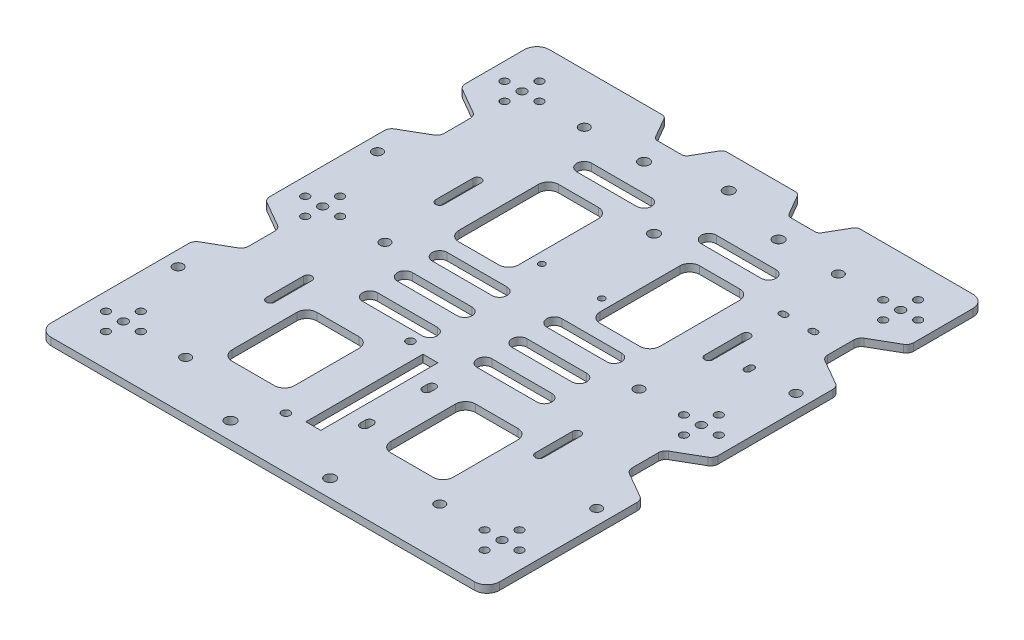
SolidWorks part; units mm, degrees
ref_plane "Front Plane" through (0, 0, 0) normal (0, 0, 1) x (1, 0, 0)
ref_plane "Top Plane" through (0, 0, 0) normal (0, 1, 0) x (1, 0, 0)
ref_plane "Right Plane" through (0, 0, 0) normal (1, 0, 0) x (0, 0, -1)
sketch "草图1" plane through (0, 0, 0) normal (0, 1, 0) x (1, 0, 0)
  line L0 (-76, 110.058) -> (-76, -117.2518) construction
  line L1 (-90, -100) -> (90, -100)
  line L2 (-90, -100) -> (-90, 100)
  line L3 (-90, 100) -> (90, 100)
  line L4 (90, -100) -> (90, 100)
  line L5 (-90, -100) -> (90, 100) construction
  line L6 (-90, 100) -> (90, -100) construction
  line L7 (0, 114.4164) -> (0, -117.2518) construction
  line L8 (-86, 80) -> (-48.9187, 80) construction
  line L9 (-76, 0) -> (-83, 0) construction
  line L10 (-76, -40) -> (18.6433, -40) construction
  line L11 (76, 0) -> (83, 0) construction
  circle A0 centre (-76, 80) radius 10 construction
  circle A2 centre (-76, 80) radius 1.75
  circle A3 centre (-83, 80) radius 1.6
  circle A4 centre (-76, 87) radius 1.6
  circle A5 centre (-69, 80) radius 1.6
  circle A6 centre (-76, 73) radius 1.6
  circle A7 centre (-76, 0) radius 1.75
  circle A8 centre (-83, 0) radius 1.6
  circle A9 centre (-76, 0) radius 10 construction
  circle A10 centre (-76, 7) radius 1.6
  circle A11 centre (-76, -7) radius 1.6
  circle A12 centre (-69, 0) radius 1.6
  circle A13 centre (-76, -80) radius 10 construction
  circle A14 centre (-76, -73) radius 1.6
  circle A15 centre (-69, -80) radius 1.6
  circle A16 centre (-76, -80) radius 1.75
  circle A17 centre (-83, -80) radius 1.6
  circle A18 centre (-76, -87) radius 1.6
  circle A19 centre (76, -80) radius 10 construction
  circle A20 centre (76, 0) radius 10 construction
  circle A21 centre (76, 80) radius 10 construction
  circle A22 centre (76, -87) radius 1.6
  circle A23 centre (83, -80) radius 1.6
  circle A24 centre (76, -80) radius 1.75
  circle A25 centre (69, -80) radius 1.6
  circle A26 centre (76, -73) radius 1.6
  circle A27 centre (69, 0) radius 1.6
  circle A28 centre (76, -7) radius 1.6
  circle A29 centre (76, 7) radius 1.6
  circle A30 centre (83, 0) radius 1.6
  circle A31 centre (76, 0) radius 1.75
  circle A32 centre (76, 73) radius 1.6
  circle A33 centre (69, 80) radius 1.6
  circle A34 centre (76, 87) radius 1.6
  circle A35 centre (83, 80) radius 1.6
  circle A36 centre (76, 80) radius 1.75
  point P0 (0, 0)
  point P31 (-76, 0)
  point P81 (76, 0)
  dimension "D4" = 20
  dimension "D5" = 20
  dimension "D6" = 3.5
  dimension "D7" = 3.2
  dimension "D8" = 14
  dimension "D9" = 3.2
  dimension "D10" = 14
  dimension "D11" = 3.5
  dimension "D12" = 80
  dimension "D13" = 3.2
  dimension "D14" = 7
  dimension "D15" = 20
  dimension "D16" = 80
  dimension "D17" = 3.2
  dimension "D18" = 7
  dimension "D19" = 20
  dimension "D1" = 200
  dimension "D2" = 180
  dimension "D3" = 14
  dimension "D21" = 40
extrude "凸台-拉伸1" add sketch "草图1" along normal blind 3
sketch "草图2" plane through (0, 3, 0) normal (0, 1, 0) x (1, 0, 0)
  line L0 (-51, 100) -> (-51, -121.0389) construction
  line L1 (90, 100) -> (-90, 100) construction
  line L2 (0, 100) -> (0, -100) construction
  line L3 (-90, -100) -> (90, -100) construction
  line L4 (-90, 100) -> (-90, -100) construction
  line L5 (-118.3864, 0) -> (145.0738, 0) construction
  line L6 (51, 100) -> (51, -121.0389) construction
  circle A0 centre (-84, 30) radius 2
  circle A1 centre (-84, -50) radius 2
  circle A3 centre (-51, 0) radius 2
  circle A4 centre (-51, -80) radius 2
  circle A5 centre (-51, 80) radius 2
  circle A6 centre (51, 80) radius 2
  circle A7 centre (51, -80) radius 2
  circle A8 centre (51, 0) radius 2
  circle A9 centre (84, -50) radius 2
  circle A10 centre (84, 30) radius 2
  dimension "D2" = 4
  dimension "D3" = 6
  dimension "D4" = 30
  dimension "D5" = 4
  dimension "D6" = 50
  dimension "D7" = 6
  dimension "D9" = 4
  dimension "D10" = 4
  dimension "D1" = 39
  dimension "D11" = 20
extrude "切除-拉伸1" cut sketch "草图2" against normal blind 3
sketch "草图3" plane through (0, 3, 0) normal (0, 1, 0) x (1, 0, 0)
  line L0 (0, 100) -> (0, -105.4254) construction
  line L1 (90, 100) -> (-90, 100) construction
  line L2 (-97.7182, 0) -> (114, 0) construction
  line L3 (-54, 25) -> (-54, 40) construction
  line L4 (-55.65, 25) -> (-55.65, 40)
  line L5 (-52.35, 25) -> (-52.35, 40)
  line L6 (-54, -43) -> (-54, -28) construction
  line L7 (-55.65, -43) -> (-55.65, -28)
  line L8 (-52.35, -43) -> (-52.35, -28)
  line L9 (54, -43) -> (54, -28) construction
  line L10 (55.65, -43) -> (55.65, -28)
  line L11 (52.35, -43) -> (52.35, -28)
  line L12 (54, 25) -> (54, 40) construction
  line L13 (55.65, 25) -> (55.65, 40)
  line L14 (52.35, 25) -> (52.35, 40)
  circle A0 centre (-54, 25) radius 1.65 construction
  circle A1 centre (-54, -43) radius 1.65 construction
  circle A2 centre (54, -43) radius 1.65 construction
  circle A3 centre (54, 25) radius 1.65 construction
  arc A4 (-55.65, 25) -> (-52.35, 25) centre (-54, 25) ccw
  arc A5 (-52.35, 40) -> (-55.65, 40) centre (-54, 40) ccw
  arc A6 (-55.65, -43) -> (-52.35, -43) centre (-54, -43) ccw
  arc A7 (-52.35, -28) -> (-55.65, -28) centre (-54, -28) ccw
  circle A8 centre (54, -43) radius 1.65 construction
  circle A9 centre (54, 25) radius 1.65 construction
  arc A10 (55.65, -43) -> (52.35, -43) centre (54, -43) cw
  arc A11 (52.35, -28) -> (55.65, -28) centre (54, -28) cw
  arc A12 (55.65, 25) -> (52.35, 25) centre (54, 25) cw
  arc A13 (52.35, 40) -> (55.65, 40) centre (54, 40) cw
  point P16 (-54, 32.5)
  point P23 (-54, -35.5)
  point P31 (54, -35.5)
  point P37 (54, 32.5)
  dimension "D1" = 3.3
  dimension "D2" = 25
  dimension "D4" = 3.3
  dimension "D5" = 68
  dimension "D6" = 108
  dimension "D3" = 108
  dimension "D7" = 3.3
  dimension "D8" = 15
  dimension "D9" = 3.3
  dimension "D10" = 15
extrude "翅膀孔位" cut sketch "草图3" against normal blind 7.5
sketch "草图4" plane through (0, 3, 0) normal (0, 1, 0) x (1, 0, 0)
  line L0 (0, 0) -> (0, 124.0114) construction
  line L1 (90, 100) -> (-90, 100) construction
  circle A0 centre (0, 87) radius 2.15
  circle A1 centre (0, 57) radius 2.15
  circle A2 centre (-27, 80) radius 2.15
  circle A3 centre (27, 80) radius 2.15
  dimension "D1" = 13
  dimension "D2" = 4.3
  dimension "D3" = 4.3
  dimension "D4" = 30
  dimension "D5" = 4.3
  dimension "D6" = 20
  dimension "D7" = 54
extrude "尾巴孔位" cut sketch "草图4" against normal blind 7.5
sketch "草图5" plane through (0, 3, 0) normal (0, 1, 0) x (1, 0, 0)
  line L0 (0, 100) -> (0, -116.1185) construction
  line L1 (90, 100) -> (-90, 100) construction
  line L3 (-4.5, -31.25) -> (1.5, -31.25)
  line L4 (-4.5, -31.25) -> (-4.5, -78.25)
  line L5 (-4.5, -78.25) -> (1.5, -78.25)
  line L6 (1.5, -31.25) -> (1.5, -78.25)
  line L7 (-4.5, -31.25) -> (1.5, -78.25) construction
  line L8 (-4.5, -78.25) -> (1.5, -31.25) construction
  line L9 (5.91, 100) -> (5.91, -116.1185) construction
  line L10 (-90, -100) -> (90, -100) construction
  point P9 (-1.5, -54.75)
  dimension "D1" = 47
  dimension "D2" = 6
  dimension "D3" = 1.5
  dimension "D4" = 45.25
  dimension "D5" = 5.91
extrude "打印件位" cut sketch "草图5" against normal blind 7.5
ref_plane "对称面" through (0, 0, 0) normal (-1, 0, 0) x (0, 0, 1)
ref_plane "线定位面" through (5.91, 0, 0) normal (-1, 0, 0) x (0, 0, 1)
sketch "草图6" plane through (0, 3, 0) normal (0, 1, 0) x (1, 0, 0)
  line L0 (-1.5, -31.25) -> (-1.5, -78.25) construction
  line L1 (1.5, -31.25) -> (-4.5, -31.25) construction
  line L2 (-4.5, -78.25) -> (1.5, -78.25) construction
  line L3 (-4.5, -31.25) -> (-4.5, -78.25) construction
  line L4 (1.5, -78.25) -> (1.5, -31.25) construction
  line L5 (-19.6713, -54.25) -> (36.5531, -54.25) construction
  line L6 (8.5, -42.75) -> (8.5, -40.75) construction
  line L7 (6.85, -42.75) -> (6.85, -40.75)
  line L8 (10.15, -42.75) -> (10.15, -40.75)
  line L9 (8.5, -65.75) -> (8.5, -67.75) construction
  line L10 (6.85, -65.75) -> (6.85, -67.75)
  line L11 (10.15, -65.75) -> (10.15, -67.75)
  circle A0 centre (8.5, -41.75) radius 1.6 construction
  circle A1 centre (8.5, -66.75) radius 1.6 construction
  circle A2 centre (-11.5, -29.25) radius 1.65
  circle A3 centre (-11.5, -79.25) radius 1.65
  arc A4 (6.85, -42.75) -> (10.15, -42.75) centre (8.5, -42.75) ccw
  arc A5 (10.15, -40.75) -> (6.85, -40.75) centre (8.5, -40.75) ccw
  arc A6 (6.85, -65.75) -> (10.15, -65.75) centre (8.5, -65.75) cw
  arc A7 (10.15, -67.75) -> (6.85, -67.75) centre (8.5, -67.75) cw
  point P22 (8.5, -41.75)
  point P29 (8.5, -66.75)
  dimension "D1" = 3.2
  dimension "D2" = 20
  dimension "D4" = 25
  dimension "D5" = 3.3
  dimension "D6" = 50
  dimension "D7" = 10
  dimension "D3" = 23
  dimension "D8" = 3.3
  dimension "D9" = 2
extrude "打印件孔位" cut sketch "草图6" against normal blind 10
sketch "草图7" plane through (0, 3, 0) normal (0, 1, 0) x (1, 0, 0)
  line L0 (0, -22.5802) -> (0, -128.6812) construction
  line L1 (0, 1.65) -> (0, -1.65) construction
  line L2 (-90, -100) -> (90, -100) construction
  circle A0 centre (-20, -93) radius 2.15
  circle A1 centre (20, -93) radius 2.15
  dimension "D1" = 40
  dimension "D2" = 7
  dimension "D3" = 4.3
extrude "头部孔位" cut sketch "草图7" against normal blind 10
sketch "草图8" plane through (0, 3, 0) normal (0, 1, 0) x (1, 0, 0)
  line L0 (0, 100) -> (0, -147.651) construction
  line L1 (90, 100) -> (-90, 100) construction
  line L2 (-98.7792, 0) -> (126.1621, 0) construction
  line L3 (-40.35, 55) -> (-16.35, 55)
  line L4 (-40.35, 55) -> (-40.35, 15)
  line L5 (-40.35, 15) -> (-16.35, 15)
  line L6 (-16.35, 55) -> (-16.35, 15)
  line L7 (-40.35, 55) -> (-16.35, 15) construction
  line L8 (-40.35, 15) -> (-16.35, 55) construction
  line L9 (-44.35, -38) -> (-19.35, -38)
  line L10 (-44.35, -38) -> (-44.35, -72)
  line L11 (-44.35, -72) -> (-19.35, -72)
  line L12 (-19.35, -38) -> (-19.35, -72)
  line L13 (-44.35, -38) -> (-19.35, -72) construction
  line L14 (-44.35, -72) -> (-19.35, -38) construction
  line L15 (-52.35, 25) -> (-52.35, 40) construction
  line L16 (-52.35, -43) -> (-52.35, -28) construction
  line L17 (-90, -100) -> (90, -100) construction
  line L18 (44.35, -72) -> (19.35, -38) construction
  line L19 (44.35, -38) -> (19.35, -72) construction
  line L20 (40.35, 15) -> (16.35, 55) construction
  line L21 (40.35, 55) -> (16.35, 15) construction
  line L22 (19.35, -38) -> (19.35, -72)
  line L23 (44.35, -72) -> (19.35, -72)
  line L24 (44.35, -38) -> (44.35, -72)
  line L25 (44.35, -38) -> (19.35, -38)
  line L26 (16.35, 55) -> (16.35, 15)
  line L27 (40.35, 15) -> (16.35, 15)
  line L28 (40.35, 55) -> (40.35, 15)
  line L29 (40.35, 55) -> (16.35, 55)
  line L30 (-35, 6) -> (-11, 6) construction
  line L31 (-35, 9) -> (-11, 9)
  line L32 (-35, 3) -> (-11, 3)
  line L33 (-35, -8) -> (-11, -8) construction
  line L34 (-35, -5) -> (-11, -5)
  line L35 (-35, -11) -> (-11, -11)
  line L36 (-111.9755, -15) -> (122.1958, -15) construction
  line L37 (-35, -22) -> (-11, -22) construction
  line L38 (-35, -25) -> (-11, -25)
  line L39 (-35, -19) -> (-11, -19)
  line L40 (35, -22) -> (11, -22) construction
  line L41 (35, -25) -> (11, -25)
  line L42 (35, -19) -> (11, -19)
  line L43 (35, -8) -> (11, -8) construction
  line L44 (35, -5) -> (11, -5)
  line L45 (35, -11) -> (11, -11)
  line L46 (35, 6) -> (11, 6) construction
  line L47 (35, 9) -> (11, 9)
  line L48 (35, 3) -> (11, 3)
  line L49 (-37, 66) -> (-13, 66) construction
  line L50 (-37, 69) -> (-13, 69)
  line L51 (-37, 63) -> (-13, 63)
  line L52 (37, 66) -> (13, 66) construction
  line L53 (37, 69) -> (13, 69)
  line L54 (37, 63) -> (13, 63)
  arc A0 (-35, 9) -> (-35, 3) centre (-35, 6) ccw
  arc A1 (-11, 3) -> (-11, 9) centre (-11, 6) ccw
  arc A2 (-35, -5) -> (-35, -11) centre (-35, -8) ccw
  arc A3 (-11, -11) -> (-11, -5) centre (-11, -8) ccw
  arc A4 (-35, -25) -> (-35, -19) centre (-35, -22) cw
  arc A5 (-11, -19) -> (-11, -25) centre (-11, -22) cw
  arc A6 (35, -25) -> (35, -19) centre (35, -22) ccw
  arc A7 (11, -19) -> (11, -25) centre (11, -22) ccw
  arc A8 (35, -5) -> (35, -11) centre (35, -8) cw
  arc A9 (11, -11) -> (11, -5) centre (11, -8) cw
  arc A10 (35, 9) -> (35, 3) centre (35, 6) cw
  arc A11 (11, 3) -> (11, 9) centre (11, 6) cw
  arc A12 (-37, 69) -> (-37, 63) centre (-37, 66) ccw
  arc A13 (-13, 63) -> (-13, 69) centre (-13, 66) ccw
  arc A14 (37, 69) -> (37, 63) centre (37, 66) cw
  arc A15 (13, 63) -> (13, 69) centre (13, 66) cw
  point P5 (-28.35, 35)
  point P11 (-31.85, -55)
  point P31 (31.85, -55)
  point P32 (28.35, 35)
  point P35 (-23, 6)
  point P42 (-23, -8)
  point P51 (-23, -22)
  point P58 (23, -22)
  point P65 (23, -8)
  point P72 (23, 6)
  point P79 (-25, 66)
  point P86 (25, 66)
  dimension "D9" = 3
  dimension "D1" = 24
  dimension "D2" = 40
  dimension "D3" = 12
  dimension "D4" = 15
  dimension "D5" = 25
  dimension "D6" = 34
  dimension "D7" = 8
  dimension "28" = 28
  dimension "D10" = 24
  dimension "D11" = 9
  dimension "D12" = 23
  dimension "D13" = 6
  dimension "D14" = 23
  dimension "D15" = 24
  dimension "D16" = 14
  dimension "D17" = 7
  dimension "D18" = 6
  dimension "D19" = 11
  dimension "D20" = 24
  dimension "D21" = 25
extrude "减重位" cut sketch "草图8" against normal blind 10
sketch "草图9" plane through (0, 3, 0) normal (0, 1, 0) x (1, 0, 0)
  line L0 (-33.8257, 0) -> (26.7162, 0) construction
  line L1 (-33.8257, 3) -> (26.7162, 3)
  line L2 (-33.8257, -3) -> (26.7162, -3)
  arc A0 (-33.8257, 3) -> (-33.8257, -3) centre (-33.8257, 0) ccw
  arc A1 (26.7162, -3) -> (26.7162, 3) centre (26.7162, 0) ccw
  point P3 (-3.5548, 0)
  dimension "D1" = 3
sketch "草图10" plane through (0, 3, 0) normal (0, 1, 0) x (1, 0, 0)
  line L0 (0, 120.7072) -> (0, -16.4674) construction
  line L1 (-38.547, 100) -> (-32.7735, 90)
  line L2 (90, 100) -> (-90, 100) construction
  line L3 (-32.7735, 90) -> (-20.7735, 90)
  line L4 (-20.7735, 90) -> (-15, 100)
  line L5 (-38.547, 100) -> (-15, 100)
  line L6 (38.547, 100) -> (32.7735, 90)
  line L7 (32.7735, 90) -> (20.7735, 90)
  line L8 (20.7735, 90) -> (15, 100)
  line L9 (38.547, 100) -> (15, 100)
  dimension "D1" = 12
  dimension "D2" = 60
  dimension "D3" = 60
  dimension "D4" = 10
  dimension "D5" = 15
extrude "切除-拉伸7" cut sketch "草图10" against normal blind 10
sketch "草图11" plane through (0, 3, 0) normal (0, 1, 0) x (1, 0, 0)
  line L0 (0, 100) -> (0, -109.0873) construction
  line L1 (15, 100) -> (-15, 100) construction
  line L2 (-90, 69.5056) -> (-77, 62)
  line L3 (-90, 100) -> (-90, -100) construction
  line L4 (-77, 62) -> (-77, 48)
  line L5 (-77, 48) -> (-90, 40.4944)
  line L6 (-90, 40.4944) -> (-90, 69.5056)
  line L7 (-77, 55) -> (38.115, 55) construction
  line L8 (-90, -8.9889) -> (-90, -38)
  line L9 (-90, -38) -> (-77, -30.4944)
  line L10 (-77, -30.4944) -> (-77, -16.4944)
  line L11 (-77, -16.4944) -> (-90, -8.9889)
  line L12 (77, -16.4944) -> (90, -8.9889)
  line L13 (77, -30.4944) -> (77, -16.4944)
  line L14 (90, -38) -> (77, -30.4944)
  line L15 (90, -8.9889) -> (90, -38)
  line L16 (90, 40.4944) -> (90, 69.5056)
  line L17 (77, 48) -> (90, 40.4944)
  line L18 (77, 62) -> (77, 48)
  line L19 (90, 69.5056) -> (77, 62)
  circle A0 centre (-76, 73) radius 1.6 construction
  circle A1 centre (-84, -50) radius 2 construction
  dimension "D1" = 60
  dimension "D2" = 60
  dimension "D3" = 14
  dimension "D4" = 13
  dimension "D5" = 18
  dimension "D6" = 60
  dimension "D7" = 60
  dimension "D8" = 14
  dimension "D9" = 13
  dimension "D10" = 12
extrude "切除-拉伸8" cut sketch "草图11" against normal blind 10
fillet "圆角1" radius 4 16 edges at (44.35, 1.5, 72) (44.35, 1.5, 38) (19.35, 1.5, 38) (19.35, 1.5, 72) (-44.35, 1.5, 72) (-19.35, 1.5, 72) (-19.35, 1.5, 38) (-44.35, 1.5, 38) (40.35, 1.5, -15) (40.35, 1.5, -55) (16.35, 1.5, -55) (16.35, 1.5, -15) (-40.35, 1.5, -15) (-16.35, 1.5, -15) (-16.35, 1.5, -55) (-40.35, 1.5, -55)
fillet "圆角2" radius 3 16 edges at (90, 1.5, -69.5056) (77, 1.5, -62) (77, 1.5, -48) (90, 1.5, -40.4944) (90, 1.5, 8.9889) (77, 1.5, 16.4944) (77, 1.5, 30.4944) (90, 1.5, 38) (-90, 1.5, 38) (-77, 1.5, 30.4944) (-77, 1.5, 16.4944) (-90, 1.5, 8.9889) (-77, 1.5, -48) (-77, 1.5, -62) (-90, 1.5, -69.5056) (-90, 1.5, -40.4944)
fillet "圆角3" radius 2 8 edges at (38.547, 1.5, -100) (32.7735, 1.5, -90) (20.7735, 1.5, -90) (15, 1.5, -100) (-15, 1.5, -100) (-20.7735, 1.5, -90) (-38.547, 1.5, -100) (-32.7735, 1.5, -90)
fillet "圆角4" radius 5 4 edges at (-90, 1.5, -100) (90, 1.5, -100) (90, 1.5, 100) (-90, 1.5, 100)
sketch "草图12" plane through (0, 0, 0) normal (0, -1, 0) x (1, 0, 0)
  line L0 (0, -100) -> (0, 106.7414) construction
  line L1 (13.8453, -100) -> (-13.8453, -100) construction
  line L2 (36.35, -15) -> (20.35, -15) construction
  line L3 (54, -55) -> (67.25, -55) construction
  line L4 (36.35, -55) -> (81.0252, -55) construction
  line L5 (53.5, -55) -> (54.5, -55) construction
  line L6 (53.5, -53.75) -> (54.5, -53.75)
  line L7 (53.5, -56.25) -> (54.5, -56.25)
  line L8 (65.5, -55) -> (66.5, -55) construction
  line L9 (65.5, -53.75) -> (66.5, -53.75)
  line L10 (65.5, -56.25) -> (66.5, -56.25)
  line L11 (66, -55) -> (66, -35.9896) construction
  line L12 (66, -28.5) -> (66, -30) construction
  line L13 (67.25, -28.5) -> (67.25, -30)
  line L14 (64.75, -28.5) -> (64.75, -30)
  line L15 (84, -30) -> (54.5, -30) construction
  circle A0 centre (12.03, -24) radius 1.25
  circle A1 centre (-12.03, -24) radius 1.25
  circle A2 centre (54, -55) radius 1.25 construction
  arc A3 (53.5, -53.75) -> (53.5, -56.25) centre (53.5, -55) ccw
  circle A4 centre (66, -55) radius 1.25 construction
  arc A5 (54.5, -56.25) -> (54.5, -53.75) centre (54.5, -55) ccw
  arc A7 (65.5, -53.75) -> (65.5, -56.25) centre (65.5, -55) ccw
  arc A8 (66.5, -56.25) -> (66.5, -53.75) centre (66.5, -55) ccw
  arc A9 (67.25, -28.5) -> (64.75, -28.5) centre (66, -28.5) ccw
  arc A10 (64.75, -30) -> (67.25, -30) centre (66, -30) ccw
  point P20 (54, -55)
  point P28 (66, -55)
  point P36 (66, -29.25)
  dimension "D1" = 2.5
  dimension "D2" = 9
  dimension "D3" = 12.03
  dimension "D4" = 2.5
  dimension "D5" = 54
  dimension "D6" = 2.5
  dimension "D7" = 66
  dimension "D8" = 2.5
  dimension "D9" = 1
  dimension "D10" = 2.5
  dimension "D11" = 1
  dimension "D12" = 2.5
  dimension "D13" = 1.5
extrude "切除-拉伸9" cut sketch "草图12" against normal blind 10
